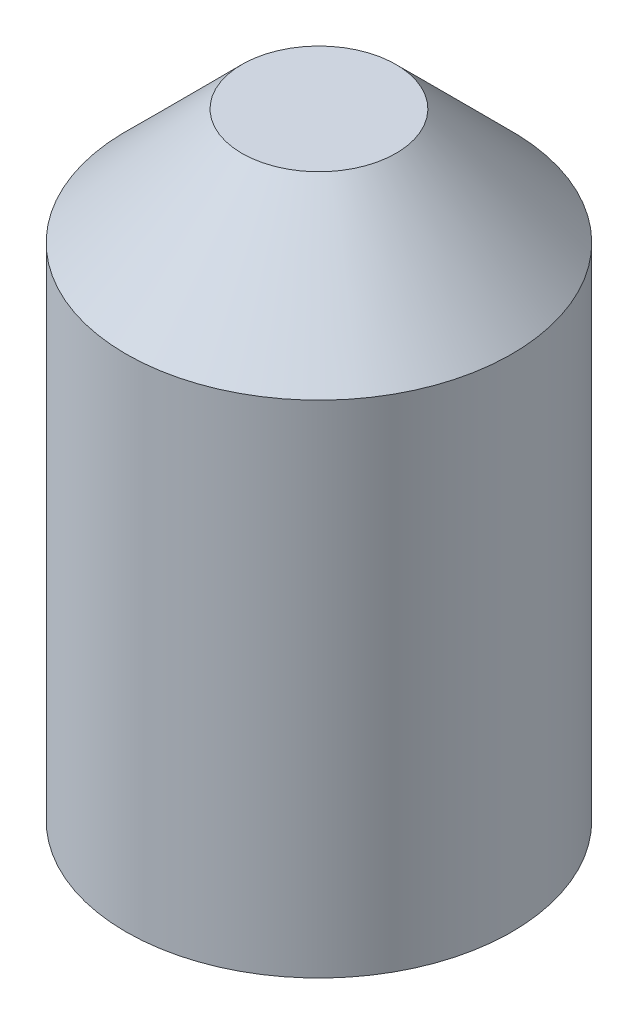
SolidWorks part; units mm, degrees
material "ASTM A36 Steel"
ref_plane "Front Plane" through (0, 0, 0) normal (0, 0, 1) x (1, 0, 0)
ref_plane "Top Plane" through (0, 0, 0) normal (0, 1, 0) x (1, 0, 0)
ref_plane "Right Plane" through (0, 0, 0) normal (1, 0, 0) x (0, 0, -1)
sketch "Sketch1" plane through (0, 0, 0) normal (0, 0, 1) x (1, 0, 0)
  line L0 (0, -6.7467) -> (0, -33.7335) construction
  line L1 (1.7272, 1.0668) -> (1.7272, 9.525)
  line L2 (1.7272, 9.525) -> (0, 10.5222)
  line L3 (0, 10.5222) -> (0, 12.7)
  line L4 (0, 12.7) -> (1.5875, 12.7)
  line L5 (1.5875, 12.7) -> (3.9751, 10.3124)
  line L6 (3.9751, 10.3124) -> (3.9751, 0)
  line L7 (3.9751, 0) -> (2.794, 0)
  line L8 (2.794, 0) -> (1.7272, 1.0668)
  dimension "D1" = 3.4544
  dimension "D2" = 60
  dimension "D3" = 45
  dimension "D4" = 3.175
  dimension "D5" = 7.9502
  dimension "D6" = 9.525
  dimension "D7" = 12.7
  dimension "D8" = 45
  dimension "D9" = 5.588
revolve "Revolve1" add sketch "Sketch1" angle 360 about L0
